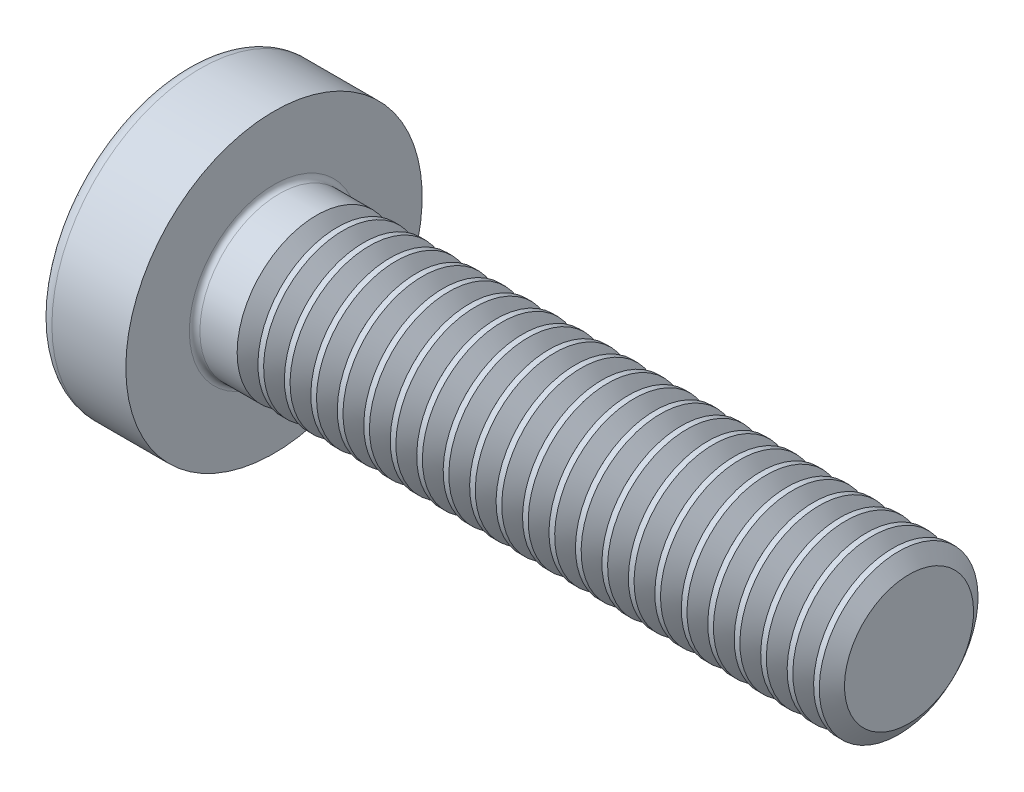
SolidWorks part; units mm, degrees
ref_plane "Plane1" through (0, 0, 0) normal (0, 0, 1) x (1, 0, 0)
ref_plane "Plane2" through (0, 0, 0) normal (0, 1, 0) x (1, 0, 0)
ref_plane "Plane3" through (0, 0, 0) normal (1, 0, 0) x (0, 0, -1)
sketch "BodySke" plane through (0, 0, 0) normal (0, 0, 1) x (1, 0, 0)
  line L0 (2.4, 1.5) -> (2.4, 2.8)
  line L1 (2.65, 6.35) -> (2.65, -3.175) construction
  line L2 (-25.4, 0) -> (127, 0) construction
  line L3 (14.4, 0) -> (0, 0)
  line L4 (2.4, 1.5) -> (14.4, 1.5)
  line L5 (14.4, 1.5) -> (14.4, 0)
  line L6 (1.0035, 2.8) -> (2.4, 2.8)
  line L8 (2.4, 6.35) -> (2.4, -3.175) construction
  arc A0 (0.7754, 2.6744) -> (0, 0) centre (5, 0) ccw
  arc A2 (0.7754, 2.6744) -> (1.0035, 2.8) centre (1.0035, 2.53) cw
  dimension "Head_crown_rad" = 5
  dimension "Head_fillet_rad" = 0.27
  dimension "Length" = 12
  dimension "Head_ht" = 2.4
  dimension "Head_dia" = 5.6
  dimension "Advance" = 0.5
  dimension "Thread_nom" = 12
  dimension "Diameter" = 3
revolve "Base-Revolve" add sketch "BodySke"
cosmetic thread "ThreadCosmetic" [suppressed]
fillet "Fillet1" radius 0.1 1 edges at (2.4, 0, 1.5)
sketch "Sketch3" plane through (0, 0, 0) normal (1, 0, 0) x (0, 0, -1)
  line L0 (0.37, -1.4) -> (-0.37, -1.4)
  line L1 (0.37, -1.4) -> (0.37, 1.4)
  line L2 (-0.37, 1.4) -> (0.37, 1.4)
  line L3 (-0.37, 1.4) -> (-0.37, -1.4)
  dimension "Cross_dia" = 2.8
  dimension "D1" = 1.4
  dimension "Cross_width" = 0.74
  dimension "D2" = 0.37
ref_plane "Plane4" through (1.75, 0, 0) normal (1, 0, 0) x (0, 0, -1)
sketch "Sketch4" plane through (1.75, 0, 0) normal (1, 0, 0) x (0, 0, -1)
  line L0 (0.37, -0.5275) -> (-0.37, -0.5275)
  line L1 (0.37, -0.5275) -> (0.37, 0.5275)
  line L2 (-0.37, 0.5275) -> (0.37, 0.5275)
  line L3 (-0.37, 0.5275) -> (-0.37, -0.5275)
  dimension "D1" = 0.74
  dimension "D2" = 1.055
  dimension "D3" = 0.37
  dimension "D4" = 0.5275
loft "Recess" cut profiles "Sketch3", "Sketch4"
pattern_circular "RecPat" count 2 every 90 about axis through (0, 0, 0) along (1, 0, 0) of "Recess"
sketch "RecCorSke" plane through (0, 0, 0) normal (0, 0, 1) x (1, 0, 0)
  line L0 (-3.175, 0) -> (15.875, 0) construction
  line L1 (-25.4, 0) -> (127, 0) construction
  line L2 (0, 0) -> (0, 0.6784)
  line L3 (0, 0.6784) -> (1.75, 0.556)
  line L4 (1.75, 0.556) -> (1.9307, 0)
  line L5 (1.9307, 0) -> (0, 0)
  dimension "Diameter" = 1.112
  dimension "Depth" = 1.75
  dimension "Draft_angle" = 4
  dimension "Bottom_angle" = 18
revolve "RecessCore" cut sketch "RecCorSke" angle 360 about L0
sketch "ThdSchSke" plane through (0, 0, 0) normal (0, 0, 1) x (1, 0, 0)
  line L0 (3.4, -1.2195) -> (3.2036, -1.5)
  line L1 (3.4, -1.2195) -> (3.5964, -1.5)
  line L2 (3.5964, -1.5) -> (3.5964, -1.875)
  line L3 (-3.175, 0) -> (5.1513, 0) construction
  line L5 (3.5964, -1.875) -> (3.2036, -1.875)
  line L6 (3.2036, -1.875) -> (3.2036, -1.5)
  dimension "Diameter" = 3
  dimension "SideAngle" = 55
  dimension "VeeAngle" = 70
  dimension "Thread_minor" = 2.439
  dimension "Overcut" = 3.75
  dimension "Start" = 3.4
revolve "ThreadSchematic" cut sketch "ThdSchSke" angle 360 about L3
pattern_linear "ThdSchPat" count 23 spacing 0.5 along (1, 0, 0) of "ThreadSchematic"
equation "\"D1@Sketch3\" = \"Cross_dia@Sketch3\" / 2"
equation "\"D2@Sketch3\" = \"Cross_width@Sketch3\" / 2"
equation "\"Depth@RecCorSke\" = \"Cross_depth@Plane4\""
equation "\"D1@Sketch4\" = \"Cross_width@Sketch3\""
equation "\"D2@Sketch4\" = \"Cross_dia@Sketch3\" - 2.0 * \"Cross_depth@Plane4\" * tan(26.5  * 0.017453292)"
equation "\"D3@Sketch4\" = \"D1@Sketch4\" / 2"
equation "\"D4@Sketch4\" = \"D2@Sketch4\" / 2"
equation "\"Thread_length@ThreadCosmetic\" = ((sgn( (\"Length@BodySke\" - \"Advance@BodySke\" * 2.0 ) - \"Thread_nom@BodySke\" )-1)*( (\"Length@BodySke\" - \"Advance@BodySke\" * 2.0 ) - \"Thread_nom@BodySke\" ))/-2+ \"Thread_nom@BodySke\""
equation "\"Thread_minor@ThdSchSke\" = \"Thread_minor@ThreadCosmetic\""
equation "\"Diameter@ThdSchSke\" = \"Diameter@BodySke\""
equation "\"Overcut@ThdSchSke\" = \"Diameter@BodySke\" * 1.25"
equation "\"Start@ThdSchSke\" = \"Head_ht@BodySke\" + \"Length@BodySke\" - \"Thread_length@ThreadCosmetic\"  '---Non-countersunk---"
equation "\"Num_threads@ThdSchPat\" = int( \"Thread_length@ThreadCosmetic\" / \"Advance@BodySke\" + 0.999 )  + 1"
equation "\"Advance@ThdSchPat\" = \"Thread_length@ThreadCosmetic\" /  (\"Num_threads@ThdSchPat\" - 1) 'relax it"
